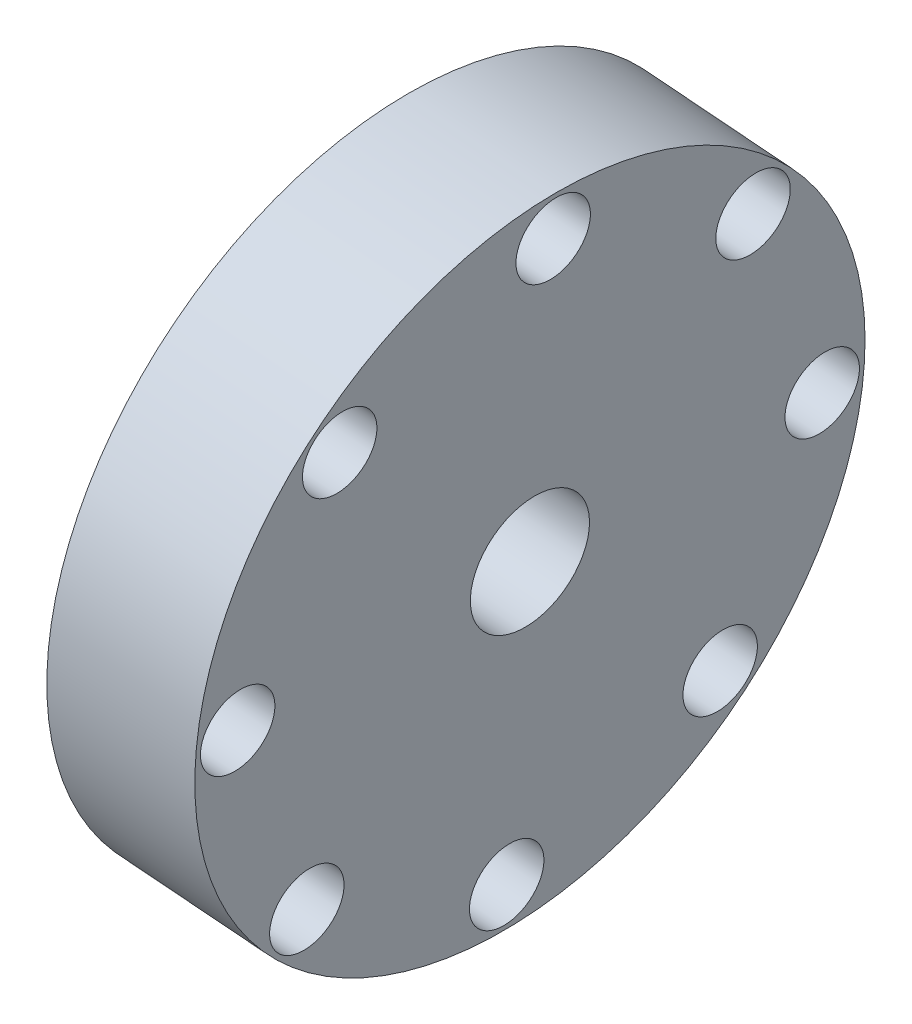
SolidWorks part; units mm, degrees
ref_plane "Front Plane" through (0, 0, 0) normal (0, 0, 1) x (1, 0, 0)
ref_plane "Top Plane" through (0, 0, 0) normal (0, 1, 0) x (1, 0, 0)
ref_plane "Right Plane" through (0, 0, 0) normal (1, 0, 0) x (0, 0, -1)
sketch "Sketch1" plane through (234.2789, -18.689, 0) normal (0.9968, -0.0795, 0) x (0, 0, -1)
  circle A1 centre (-43.1743, 8.5503) radius 14.2875
  dimension "D1" = 28.575
extrude "Boss-Extrude1" add sketch "Sketch1" against normal blind 6.35
sketch "Sketch2" plane through (234.2789, -18.689, 0) normal (0.9968, -0.0795, 0) x (0, 0, -1)
  circle A0 centre (-43.1743, 8.5503) radius 2.54
extrude "Cut-Extrude1" cut sketch "Sketch2" against normal blind 5.08
sketch "Sketch3" plane through (227.949, -18.1841, 0) normal (-0.9968, 0.0795, 0) x (0, 0, 1)
  circle A0 centre (43.1743, 21.0503) radius 1.5875
  circle A1 centre (43.1743, 8.5503) radius 14.2875 construction
  circle A2 centre (43.1743, 8.5503) radius 14.2875
  circle A3 centre (52.0131, 17.3892) radius 1.5875
  circle A4 centre (55.6743, 8.5503) radius 1.5875
  circle A5 centre (52.0131, -0.2885) radius 1.5875
  circle A6 centre (43.1743, -3.9497) radius 1.5875
  circle A7 centre (34.3354, -0.2885) radius 1.5875
  circle A8 centre (30.6743, 8.5503) radius 1.5875
  circle A9 centre (34.3354, 17.3892) radius 1.5875
  point P21 (43.1743, 8.5503)
  dimension "D1" = 3.175
  dimension "D3" = 12.5
  dimension "D2" = 8
extrude "Cut-Extrude2" cut sketch "Sketch3" against normal blind 10 contours A8 | A0 | A3 | A4 | A5 | A6 | A7 | A9
sketch "Sketch4" plane through (234.2789, -18.689, 0) normal (0.9968, -0.0795, 0) x (0, 0, -1)
  line L0 (-57.4618, 8.5503) -> (-28.8868, 8.5503) construction
  circle A0 centre (-43.1743, 8.5503) radius 14.2875 construction
